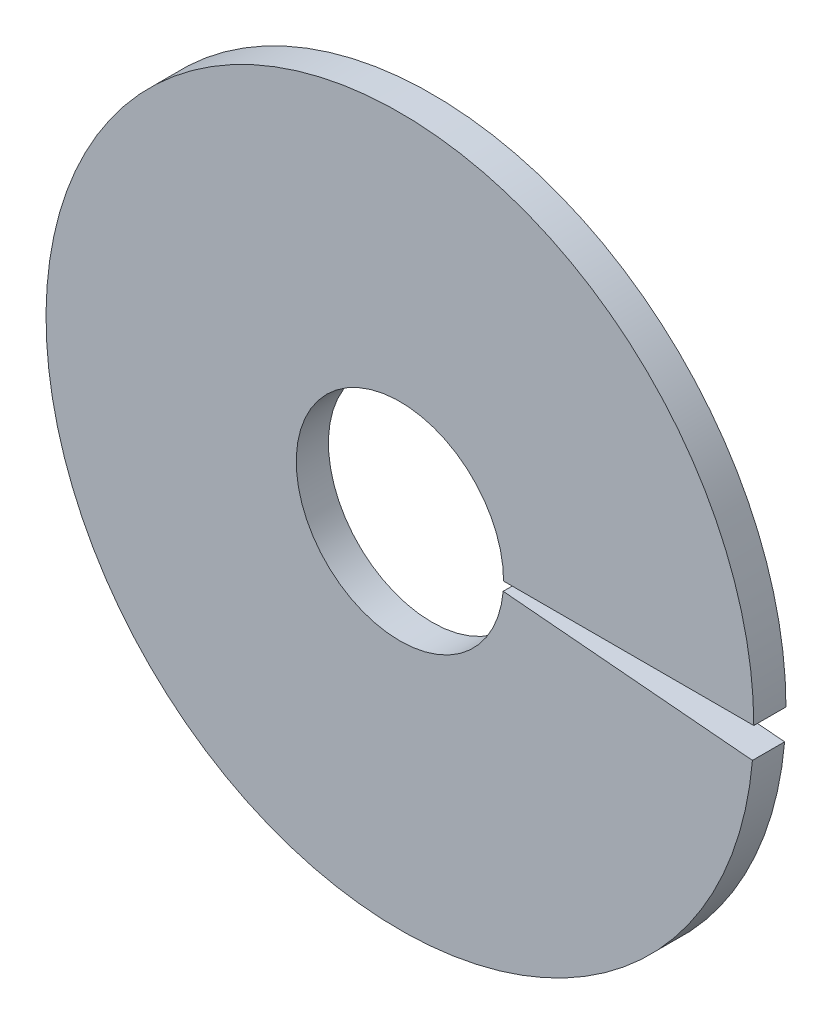
SolidWorks part; units mm, degrees
ref_plane "Front Plane" through (0, 0, 0) normal (0, 0, 1) x (1, 0, 0)
ref_plane "Top Plane" through (0, 0, 0) normal (0, 1, 0) x (1, 0, 0)
ref_plane "Right Plane" through (0, 0, 0) normal (1, 0, 0) x (0, 0, -1)
sketch "Sketch3" plane through (0, 0, 0) normal (0, 1, 0) x (1, 0, 0)
  line L1 (2.9, -0.0487) -> (9.9, -0.0487)
  line L2 (2.9, -0.0487) -> (2.9, 0.8513)
  line L3 (2.9, 0.8513) -> (9.9, 0.8513)
  line L4 (9.9, -0.0487) -> (9.9, 0.8513)
  dimension "D1" = 7
  dimension "D2" = 0.9
  dimension "D3" = 2.9
ref_axis "Axis1" through (0, 0, -2.3516) along (0, 0, 1)
revolve "Revolve1" add sketch "Sketch3" angle 355 about axis through (0, 0, -2.3516) along (0, 0, 1)
